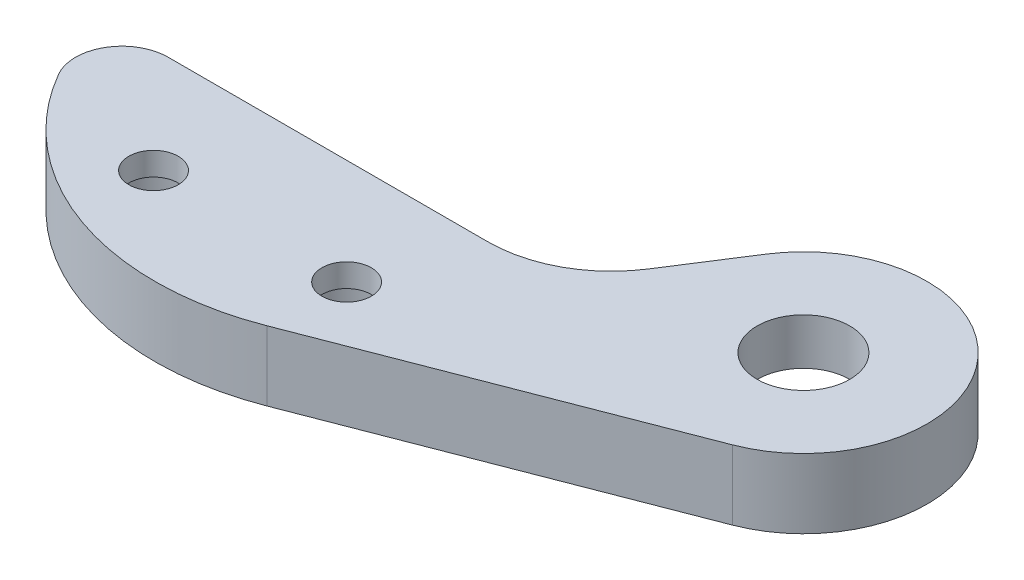
SolidWorks part; units mm, degrees
ref_plane "Спереди" through (0, 0, 0) normal (0, 0, 1) x (1, 0, 0)
ref_plane "Сверху" through (0, 0, 0) normal (0, 1, 0) x (1, 0, 0)
ref_plane "Справа" through (0, 0, 0) normal (1, 0, 0) x (0, 0, -1)
ref_plane "Плоскость4" through (0, 0, 0) normal (0, -1, 0) x (1, 0, 0)
sketch "Эскиз1" plane through (0, 0, 0) normal (0, -1, 0) x (1, 0, 0)
  line L0 (-12.1244, 4) -> (12.9364, 4)
  line L1 (12.9364, 4) -> (18.2638, -4.3156)
  line L2 (27.88, 7.4636) -> (6.12, 15.8602)
  arc A0 (6.12, 15.8602) -> (-14.7224, 8.5) centre (0, 0) ccw
  arc A1 (-14.7224, 8.5) -> (-12.1244, 4) centre (-12.1244, 7) ccw
  arc A2 (18.2638, -4.3156) -> (27.88, 7.4636) centre (25, 0) ccw
extrude "Бобышка-Вытянуть1" add sketch "Эскиз1" against normal blind 4.5
hole_wizard "Цековка для винта с заклепочной головкой M31" positions "Эскиз3" profile "Эскиз2" counterbore size "M3" standard "Ansi Metric"
sketch "Эскиз3" plane through (0, 4.5, 0) normal (0, 1, 0) x (1, 0, 0)
  point P0 (-6.25, -10.8253)
  point P1 (6.25, -10.8253)
sketch "Эскиз2" plane through (-6.25, 4.5, 10.8253) normal (1, 0, 0) x (0, 0, 1)
  line L0 (0, 0) -> (0, 4.5)
  line L1 (0, 4.5) -> (1.6, 4.5)
  line L3 (1.6, 4.5) -> (1.6, 3)
  line L4 (1.6, 3) -> (3.025, 3)
  line L5 (3.025, 3) -> (3.025, 0)
  line L7 (3.025, 0) -> (0, 0)
  line L11 (0, -6.35) -> (0, 107.95) construction
  dimension "Диаметр сквозного отверстия" = 3.2
  dimension "Глубина сквозного отверстия" = 4.5
  dimension "Диаметр цековки" = 6.05
  dimension "Глубина цековки" = 3
hole_wizard "Отверстие1" positions "Эскиз5" profile "Эскиз4" legacy
sketch "Эскиз5" plane through (0, 4.5, 0) normal (0, 1, 0) x (1, 0, 0)
  point P0 (25, 0)
sketch "Эскиз4" plane through (25, 4.5, 0) normal (1, 0, 0) x (0, 0, 1)
  line L0 (0, 0) -> (0, 4.5)
  line L1 (0, 4.5) -> (3, 4.5)
  line L2 (3, 4.5) -> (3, 1.5)
  line L3 (3, 1.5) -> (5.25, 1.5)
  line L4 (5.25, 1.5) -> (5.25, 0)
  line L5 (5.25, 0) -> (0, 0)
  line L6 (0, 110) -> (0, -10) construction
  dimension "Диаметр" = 6
  dimension "Глубина" = 4.5
  dimension "Диа. цековки" = 10.5
  dimension "Глуб. цековки" = 1.5
fillet "Скругление1" radius 8 1 edges at (12.9364, 2.25, 4)
mirror "Зеркальное отражение1" about plane through (0, 0, 0) normal (0, -1, 0) of bodies 105
delete or keep bodies "Тело-Удалить/Сохранить 1" type delete bodies bodies 105
